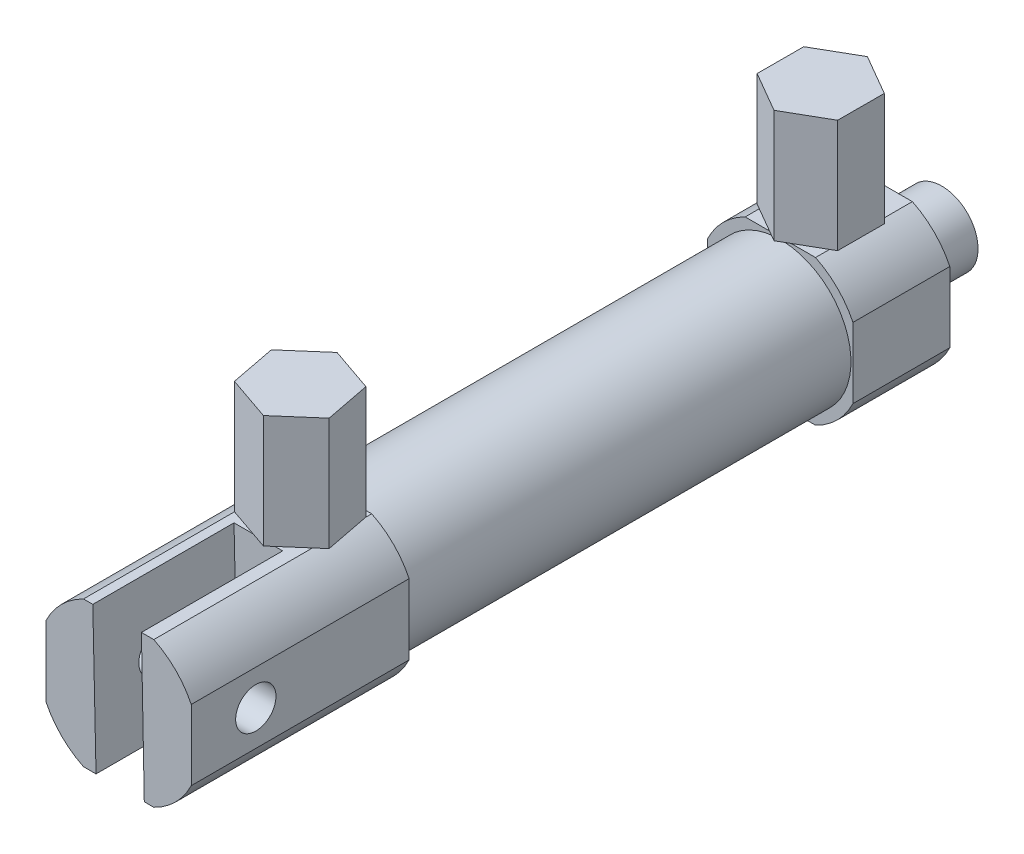
SolidWorks part; units mm, degrees
ref_plane "Front Plane" through (0, 0, 0) normal (0, 0, 1) x (1, 0, 0)
ref_plane "Top Plane" through (0, 0, 0) normal (0, 1, 0) x (1, 0, 0)
ref_plane "Right Plane" through (0, 0, 0) normal (1, 0, 0) x (0, 0, -1)
sketch "Sketch1" plane through (0, 0, 0) normal (0, 0, 1) x (1, 0, 0)
  circle A0 centre (0, 0) radius 8.75
  dimension "D1" = 17.5
extrude "Boss-Extrude1" add sketch "Sketch1" along normal blind 55
sketch "Sketch2" plane through (0, 0, 55) normal (0, 0, 1) x (1, 0, 0)
  circle A0 centre (0, 0) radius 10
  dimension "D1" = 20
extrude "Boss-Extrude2" add sketch "Sketch2" along normal blind 27
sketch "Sketch3" plane through (0, 0, 0) normal (0, 0, -1) x (-1, 0, 0)
  circle A0 centre (0, 0) radius 10
  dimension "D1" = 20
extrude "Boss-Extrude3" add sketch "Sketch3" along normal blind 12
sketch "Sketch4" plane through (0, 0, -12) normal (0, 0, -1) x (-1, 0, 0)
  circle A0 centre (0, 0) radius 4.5
  dimension "D1" = 9
extrude "Boss-Extrude4" add sketch "Sketch4" along normal blind 8
sketch "Sketch5" plane through (0, 0, 82) normal (0, 0, 1) x (1, 0, 0)
  line L0 (-9, 4.3589) -> (-9, -4.3589)
  line L1 (9, 4.3589) -> (9, -4.3589)
  circle A0 centre (0, 0) radius 10 construction
  arc A1 (-9, 4.3589) -> (-9, -4.3589) centre (0, 0) ccw
  arc A2 (9, -4.3589) -> (9, 4.3589) centre (0, 0) ccw
  dimension "D1" = 9
  dimension "D2" = 9
extrude "Cut-Extrude1" cut sketch "Sketch5" along a picked direction on the side against the normal blind 121.5
sketch "Sketch6" plane through (0, 0, 82) normal (0, 0, 1) x (1, 0, 0)
  line L0 (-3.2116, 9.4702) -> (-2.7869, -9.6038)
  line L1 (2.8106, 9.5969) -> (3.1883, -9.4781)
  arc A0 (-9, -4.3589) -> (9, -4.3589) centre (0, 0) ccw construction
  arc A1 (9, 4.3589) -> (-9, 4.3589) centre (0, 0) ccw construction
  arc A2 (-2.7869, -9.6038) -> (3.1883, -9.4781) centre (0, 0) ccw
  arc A3 (2.8106, 9.5969) -> (-3.2116, 9.4702) centre (0, 0) ccw
  dimension "D1" = 3
  dimension "D2" = 3
extrude "Cut-Extrude2" cut sketch "Sketch6" against normal blind 17.5
sketch "Sketch7" plane through (9, 0, 0) normal (1, 0, 0) x (0, 0, -1)
  line L0 (-55, -8.75) -> (-55, 8.75) construction
  circle A0 centre (-74, 0) radius 2.5
  dimension "D1" = 5
  dimension "D2" = 19
extrude "Cut-Extrude3" cut sketch "Sketch7" against normal through all
sketch "Sketch8" plane through (0, 0, -20) normal (0, 0, -1) x (-1, 0, 0)
  circle A0 centre (0, 0) radius 2.5
  dimension "D1" = 5
extrude "Cut-Extrude4" cut sketch "Sketch8" against normal blind 56.5
sketch "Sketch9" plane through (0, 0, 82) normal (0, 0, 1) x (1, 0, 0)
  line L0 (-4.3589, 9) -> (4.3589, 9)
  line L1 (-4.3589, -9) -> (4.3589, -9)
  arc A0 (-3.2116, 9.4702) -> (-9, 4.3589) centre (0, 0) ccw construction
  arc A1 (2.8106, 9.5969) -> (-3.2116, 9.4702) centre (0, 0) ccw construction
  arc A2 (9, 4.3589) -> (2.8106, 9.5969) centre (0, 0) ccw construction
  arc A3 (3.1883, -9.4781) -> (9, -4.3589) centre (0, 0) ccw construction
  arc A4 (-2.7869, -9.6038) -> (3.1883, -9.4781) centre (0, 0) ccw construction
  arc A5 (-9, -4.3589) -> (-2.7869, -9.6038) centre (0, 0) ccw construction
  arc A6 (-3.2116, 9.4702) -> (-4.3589, 9) centre (0, 0) ccw
  arc A7 (2.8106, 9.5969) -> (-3.2116, 9.4702) centre (0, 0) ccw
  arc A8 (4.3589, 9) -> (2.8106, 9.5969) centre (0, 0) ccw
  arc A9 (3.1883, -9.4781) -> (4.3589, -9) centre (0, 0) ccw
  arc A10 (-2.7869, -9.6038) -> (3.1883, -9.4781) centre (0, 0) ccw
  arc A11 (-4.3589, -9) -> (-2.7869, -9.6038) centre (0, 0) ccw
  dimension "D1" = 9
  dimension "D2" = 9
extrude "Cut-Extrude5" cut sketch "Sketch9" against normal blind 133.5
sketch "Sketch10" plane through (0, 9, 0) normal (0, 1, 0) x (1, 0, 0)
  line L0 (4.3589, 12) -> (-4.3589, 12) construction
  circle A0 centre (0, 5) radius 1.5
  dimension "D2" = 3
  dimension "D1" = 7
extrude "Cut-Extrude6" cut sketch "Sketch10" against normal blind 2
sketch "Sketch11" plane through (0, 9, 0) normal (0, 1, 0) x (1, 0, 0)
  line L0 (-4.3589, -55) -> (4.3589, -55) construction
  line L2 (-4.3589, -55) -> (4.3589, -55)
  circle A0 centre (0, -59.5) radius 1.5
  dimension "D2" = 4.5
extrude "Cut-Extrude7" cut sketch "Sketch11" against normal blind 2 contours A0
sketch "Sketch13" plane through (0, 9, 0) normal (0, 1, 0) x (1, 0, 0)
  line L1 (4.9937, 2.1024) -> (5.0063, 7.8758)
  line L2 (5.0063, 7.8758) -> (0.0126, 10.7735)
  line L3 (0.0126, 10.7735) -> (-4.9937, 7.8976)
  line L4 (-4.9937, 7.8976) -> (-5.0063, 2.1242)
  line L5 (-5.0063, 2.1242) -> (-0.0126, -0.7735)
  line L6 (-0.0126, -0.7735) -> (4.9937, 2.1024)
  circle A0 centre (0, 5) radius 5 construction
  dimension "D1" = 10
extrude "Boss-Extrude5" add sketch "Sketch13" along normal blind 14
sketch "Sketch14" plane through (0, 9, 0) normal (0, 1, 0) x (1, 0, 0)
  line L1 (1.1043, -65.1669) -> (5.4598, -61.3771)
  line L2 (5.4598, -61.3771) -> (4.3555, -55.7102)
  line L3 (4.3555, -55.7102) -> (-1.1043, -53.8331)
  line L4 (-1.1043, -53.8331) -> (-5.4598, -57.6229)
  line L5 (-5.4598, -57.6229) -> (-4.3555, -63.2898)
  line L6 (-4.3555, -63.2898) -> (1.1043, -65.1669)
  circle A0 centre (0, -59.5) radius 5 construction
  dimension "D1" = 10
extrude "Boss-Extrude6" add sketch "Sketch14" along normal blind 14
